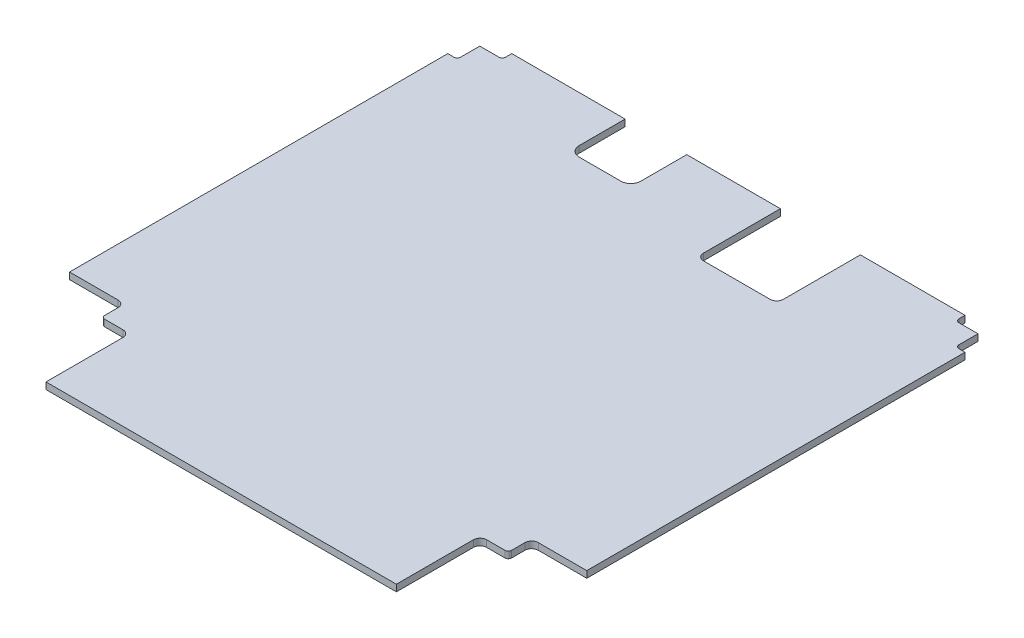
SolidWorks part; units mm, degrees
ref_plane "Front Plane" through (0, 0, 0) normal (0, 0, 1) x (1, 0, 0)
ref_plane "Top Plane" through (0, 0, 0) normal (0, 1, 0) x (1, 0, 0)
ref_plane "Right Plane" through (0, 0, 0) normal (1, 0, 0) x (0, 0, -1)
sketch "Sketch1" plane through (0, 0, 0) normal (0, 1, 0) x (1, 0, 0)
  line L1 (-170, 170) -> (170, 170)
  line L2 (-170, 170) -> (-170, -170)
  line L3 (-170, -170) -> (170, -170)
  line L4 (170, 170) -> (170, -170)
  line L5 (-170, 170) -> (170, -170) construction
  line L6 (-170, -170) -> (170, 170) construction
  point P0 (0, 0)
  dimension "D1" = 340
extrude "Boss-Extrude1" add sketch "Sketch1" along normal blind 4
sketch "Sketch2" plane through (0, 0, 0) normal (0, -1, 0) x (1, 0, 0)
  line L0 (170, -170) -> (-170, -170) construction
  line L2 (-66.9861, -170) -> (-31.9861, -170)
  line L3 (-66.9861, -170) -> (-66.9861, -127.64) construction
  line L4 (-61.9861, -122.64) -> (-36.9861, -122.64)
  line L5 (-31.9861, -170) -> (-31.9861, -127.64)
  line L8 (-61.9861, -121.64) -> (-36.9861, -121.64)
  line L9 (-30.9861, -171) -> (-30.9861, -127.64)
  line L10 (-67.9861, -171) -> (-30.9861, -171)
  line L11 (-67.9861, -171) -> (-67.9861, -127.64)
  arc A0 (-66.9861, -127.64) -> (-61.9861, -122.64) centre (-61.9861, -127.64) cw
  arc A1 (-36.9861, -122.64) -> (-31.9861, -127.64) centre (-36.9861, -127.64) cw
  arc A2 (-36.9861, -121.64) -> (-30.9861, -127.64) centre (-36.9861, -127.64) cw
  arc A3 (-67.9861, -127.64) -> (-61.9861, -121.64) centre (-61.9861, -127.64) cw
  line M8 (-170, -170) -> (170, -170)
  dimension "D1" = 5
  dimension "D2" = 1
extrude "Cut-Extrude1" cut sketch "Sketch2" against normal blind 10 contours L3 L5 A1 L4 A0 M8 | L3 A0 L4 A1 L5 L9 A2 L8 A3 L11 M8
sketch "Sketch3" plane through (0, 0, 0) normal (0, -1, 0) x (1, 0, 0)
  line L0 (-170, 100.758) -> (-155.5269, 92.4019)
  line L1 (-170, -170) -> (-170, 170) construction
  line L2 (-105.14, 148.0909) -> (-105.14, 171)
  line L3 (-154.0269, 92) -> (-126.1033, 92)
  line L4 (-123.1033, 95) -> (-123.1033, 103)
  line L5 (-120.1033, 106) -> (-109.14, 106)
  line L6 (-106.14, 109) -> (-106.14, 148)
  line L7 (-106.14, 148) -> (-110.1722, 170)
  line L8 (-170, 170) -> (170, 170) construction
  line L9 (-109.3389, 171) -> (-105.14, 171)
  line L10 (-154.0269, 91) -> (-171, 91)
  line L11 (-171, 91) -> (-171, 100.1806)
  line L14 (-110.1722, 170) -> (-170, 170) construction
  line L15 (-170, 170) -> (-170, 100.758)
  line L16 (-171, 171) -> (-171, 100.1806)
  line L18 (-154.0269, 91) -> (-126.1033, 91)
  line L19 (-122.1033, 95) -> (-122.1033, 103)
  line L20 (-120.1033, 105) -> (-109.14, 105)
  line L21 (-105.14, 109) -> (-105.14, 148.0909)
  line L23 (-109.3389, 171) -> (-171, 171)
  line L24 (-105.14, 148.0909) -> (-109.3389, 171) construction
  line L25 (-171, 100.1806) -> (-156.0269, 91.5359) construction
  arc A0 (-109.14, 106) -> (-106.14, 109) centre (-109.14, 109) ccw
  arc A1 (-123.1033, 103) -> (-120.1033, 106) centre (-120.1033, 103) cw
  arc A2 (-126.1033, 92) -> (-123.1033, 95) centre (-126.1033, 95) ccw
  arc A3 (-154.0269, 92) -> (-155.5269, 92.4019) centre (-154.0269, 95) cw
  arc A5 (-126.1033, 91) -> (-122.1033, 95) centre (-126.1033, 95) ccw
  arc A6 (-122.1033, 103) -> (-120.1033, 105) centre (-120.1033, 103) cw
  arc A7 (-109.14, 105) -> (-105.14, 109) centre (-109.14, 109) ccw
  arc A8 (-154.0269, 91) -> (-156.0269, 91.5359) centre (-154.0269, 95) cw construction
  dimension "D1" = 3
  dimension "D2" = 1
extrude "Cut-Extrude2" cut sketch "Sketch3" against normal blind 10
mirror "Mirror1" about plane through (0, 0, 0) normal (1, 0, 0) of "Cut-Extrude2"
sketch "Sketch4" plane through (0, 0, 0) normal (0, -1, 0) x (1, 0, 0)
  line L0 (170, -170) -> (-30.9861, -170) construction
  line L1 (26.2061, -170) -> (72.2061, -170)
  line L2 (26.2061, -170) -> (26.2061, -109)
  line L3 (29.2061, -106) -> (69.2061, -106)
  line L4 (72.2061, -170) -> (72.2061, -109)
  line L8 (29.2061, -105) -> (69.2061, -105)
  line L9 (73.2061, -171) -> (73.2061, -109)
  line L10 (25.2061, -171) -> (73.2061, -171)
  line L11 (25.2061, -171) -> (25.2061, -109)
  arc A0 (69.2061, -106) -> (72.2061, -109) centre (69.2061, -109) cw
  arc A1 (26.2061, -109) -> (29.2061, -106) centre (29.2061, -109) cw
  arc A2 (69.2061, -105) -> (73.2061, -109) centre (69.2061, -109) cw
  arc A3 (25.2061, -109) -> (29.2061, -105) centre (29.2061, -109) cw
  line M26 (-30.9861, -170) -> (170, -170)
  dimension "D1" = 3
  dimension "D2" = 1
extrude "Cut-Extrude3" cut sketch "Sketch4" against normal blind 10 contours A1 L2 L4 A0 L3 M26 | A3 L11 L2 A1 L3 A0 L4 L9 A2 L8 M26
sketch "Sketch5" plane through (0, 0, 0) normal (0, -1, 0) x (1, 0, 0)
  line L0 (136, -170) -> (136, -149.5)
  line L1 (170, -170) -> (73.2061, -170) construction
  line L2 (136, -149.5) -> (149.5, -149.5)
  line L3 (149.5, -149.5) -> (149.5, -136)
  line L4 (149.5, -136) -> (170, -136)
  line L5 (170, 91) -> (170, -170) construction
  line L6 (170, -136) -> (170, -170)
  line L7 (170, -170) -> (136, -170)
  line L8 (-170, -136) -> (-149.5, -136)
  line L9 (-170, -170) -> (-170, 91) construction
  line L10 (-149.5, -136) -> (-149.5, -149.5)
  line L11 (-149.5, -149.5) -> (-136, -149.5)
  line L12 (-136, -149.5) -> (-136, -170)
  line L13 (-67.9861, -170) -> (-170, -170) construction
  line L14 (-136, -170) -> (-170, -170)
  line L15 (-170, -170) -> (-170, -136)
  dimension "D1" = 20.5
  dimension "D2" = 13.5
  dimension "D3" = 20.5
  dimension "D4" = 13.5
extrude "Cut-Extrude4" cut sketch "Sketch5" against normal blind 10
fillet "Fillet1" radius 2 4 edges at (-149.5, 2, -136) (-136, 2, -149.5) (136, 2, -149.5) (149.5, 2, -136)
sketch "Sketch6" plane through (0, 0, 0) normal (0, 1, 0) x (1, 0, 0)
  line L0 (-105.14, -170) -> (105.14, -170) construction
  line L1 (155.2, -155.2) -> (-155.2, -155.2)
  line L2 (155.2, -155.2) -> (155.2, 155.2)
  line L3 (155.2, 155.2) -> (-155.2, 155.2)
  line L4 (-155.2, -155.2) -> (-155.2, 155.2)
  line L5 (155.2, -155.2) -> (-155.2, 155.2) construction
  line L6 (155.2, 155.2) -> (-155.2, -155.2) construction
  line L7 (170, -91) -> (170, 136) construction
  line L9 (196.1908, 192.1317) -> (-196.1908, 192.1317)
  line L10 (196.1908, 192.1317) -> (196.1908, -192.1317)
  line L11 (196.1908, -192.1317) -> (-196.1908, -192.1317)
  line L12 (-196.1908, 192.1317) -> (-196.1908, -192.1317)
  line L13 (196.1908, 192.1317) -> (-196.1908, -192.1317) construction
  line L14 (196.1908, -192.1317) -> (-196.1908, 192.1317) construction
  point P0 (0, 0)
  point P10 (0, 0)
  dimension "D1" = 14.8
  dimension "D2" = 14.8
extrude "Cut-Extrude5" cut sketch "Sketch6" along normal blind 10
